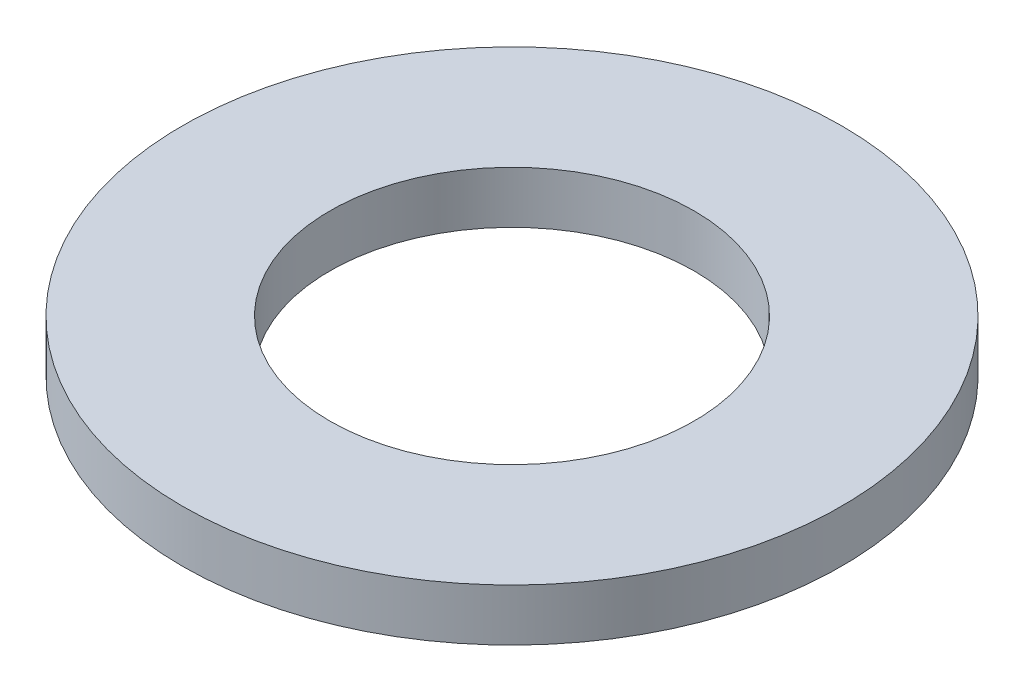
SolidWorks part; units mm, degrees
material "1.4000 (X6Cr13)"
ref_plane "Front Plane" through (0, 0, 0) normal (0, 0, 1) x (1, 0, 0)
ref_plane "Top Plane" through (0, 0, 0) normal (0, 1, 0) x (1, 0, 0)
ref_plane "Right Plane" through (0, 0, 0) normal (1, 0, 0) x (0, 0, -1)
sketch "Sketch1" plane through (0, 0, 0) normal (0, 1, 0) x (1, 0, 0)
  circle A0 centre (0, 0) radius 21
  circle A1 centre (0, 0) radius 38
extrude "Boss-Extrude1" add sketch "Sketch1" along normal blind 6
